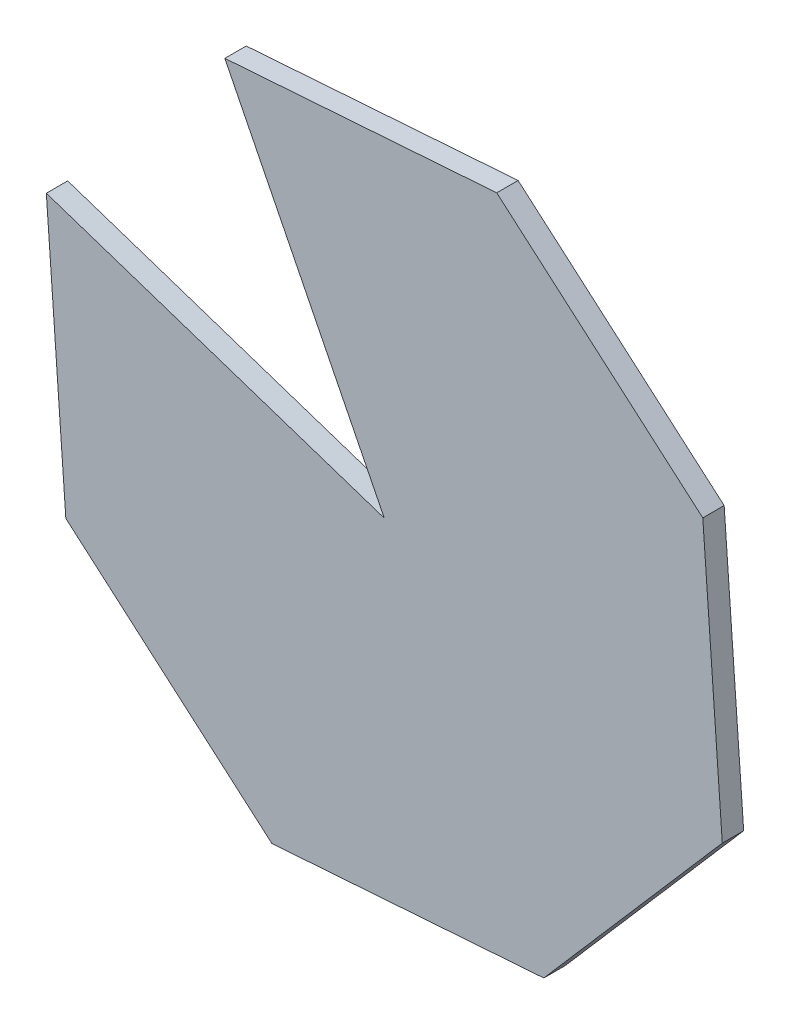
SolidWorks part; units mm, degrees
ref_plane "Front Plane" through (0, 0, 0) normal (0, 0, 1) x (1, 0, 0)
ref_plane "Top Plane" through (0, 0, 0) normal (0, 1, 0) x (1, 0, 0)
ref_plane "Right Plane" through (0, 0, 0) normal (1, 0, 0) x (0, 0, -1)
sketch "Sketch1" plane through (0, 0, 0) normal (0, 0, 1) x (1, 0, 0)
  line L0 (0, 0) -> (-22.3886, 44.7074)
  line L1 (15.7818, 47.444) -> (-22.3886, 44.7074)
  line L3 (-47.444, 15.7818) -> (-44.7074, -22.3886)
  line L4 (-44.7074, -22.3886) -> (-15.7818, -47.444)
  line L5 (-15.7818, -47.444) -> (22.3886, -44.7074)
  line L6 (22.3886, -44.7074) -> (47.444, -15.7818)
  line L7 (47.444, -15.7818) -> (44.7074, 22.3886)
  line L8 (44.7074, 22.3886) -> (15.7818, 47.444)
  line L9 (0, 0) -> (-47.444, 15.7818)
  line L11 (-22.3886, 44.7074) -> (-47.444, 15.7818) [skipped]
  circle A0 centre (0, 0) radius 50 construction
extrude "Boss-Extrude2" add sketch "Sketch1" along normal blind 3
